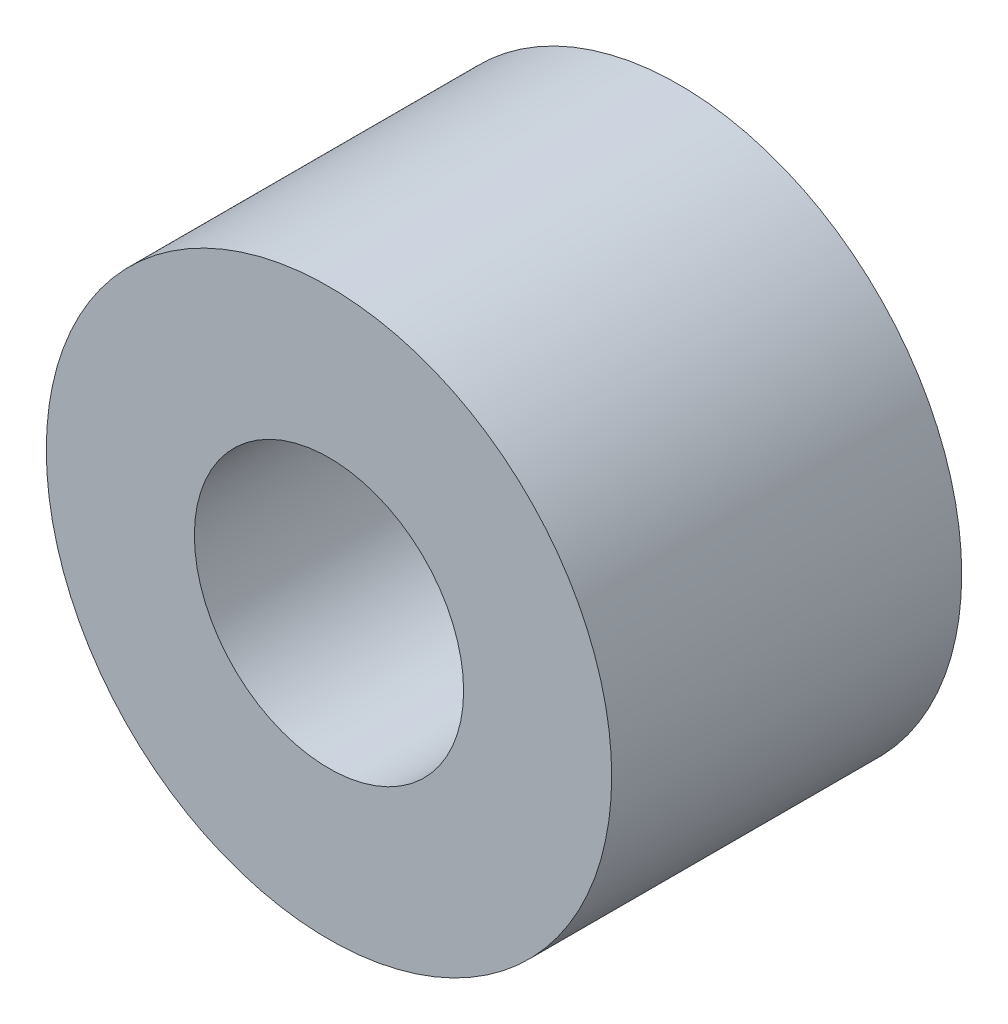
SolidWorks part; units mm, degrees
material "Brass"
ref_plane "Front Plane" through (0, 0, 0) normal (0, 0, 1) x (1, 0, 0)
ref_plane "Top Plane" through (0, 0, 0) normal (0, 1, 0) x (1, 0, 0)
ref_plane "Right Plane" through (0, 0, 0) normal (1, 0, 0) x (0, 0, -1)
sketch "Sketch1" plane through (0, 0, 0) normal (0, 0, 1) x (1, 0, 0)
  circle A0 centre (0, 0) radius 10
  circle A1 centre (0, 0) radius 21
  dimension "D1" = 20
  dimension "D2" = 42
extrude "Boss-Extrude1" add sketch "Sketch1" along normal blind 26
